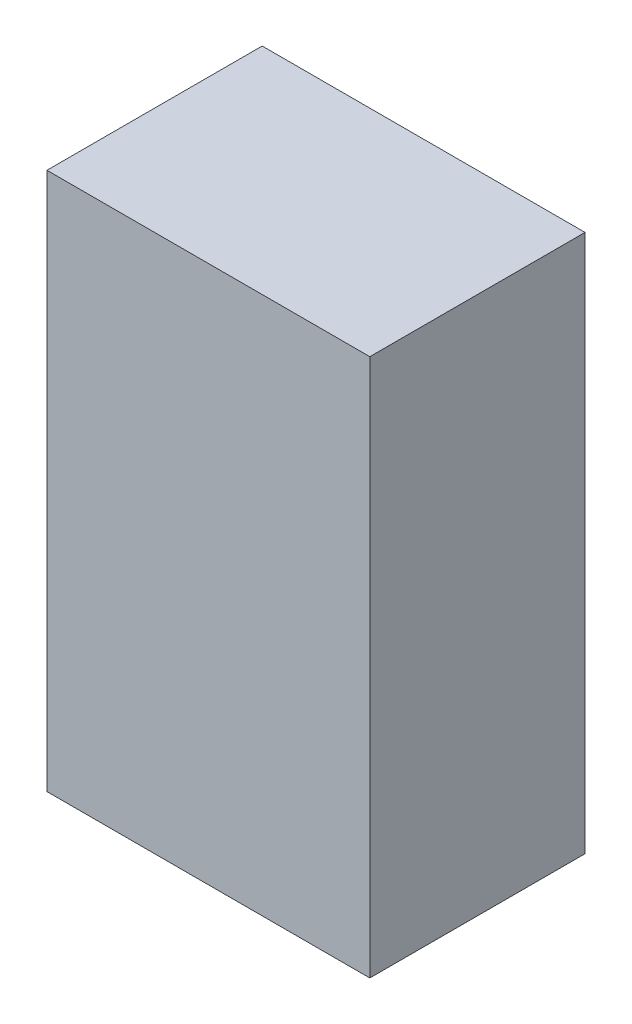
SolidWorks part; units mm, degrees
ref_plane "Front Plane" through (0, 0, 0) normal (0, 0, 1) x (1, 0, 0)
ref_plane "Top Plane" through (0, 0, 0) normal (0, 1, 0) x (1, 0, 0)
ref_plane "Right Plane" through (0, 0, 0) normal (1, 0, 0) x (0, 0, -1)
sketch "Sketch1" plane through (0, 0, 0) normal (0, 0, 1) x (1, 0, 0)
  line L1 (-6, -10) -> (6, -10)
  line L2 (-6, -10) -> (-6, 10)
  line L3 (-6, 10) -> (6, 10)
  line L4 (6, -10) -> (6, 10)
  line L5 (-6, -10) -> (6, 10) construction
  line L6 (-6, 10) -> (6, -10) construction
  point P0 (0, 0)
  dimension "D1" = 12
  dimension "D2" = 20
extrude "Boss-Extrude1" add sketch "Sketch1" along normal blind 8
